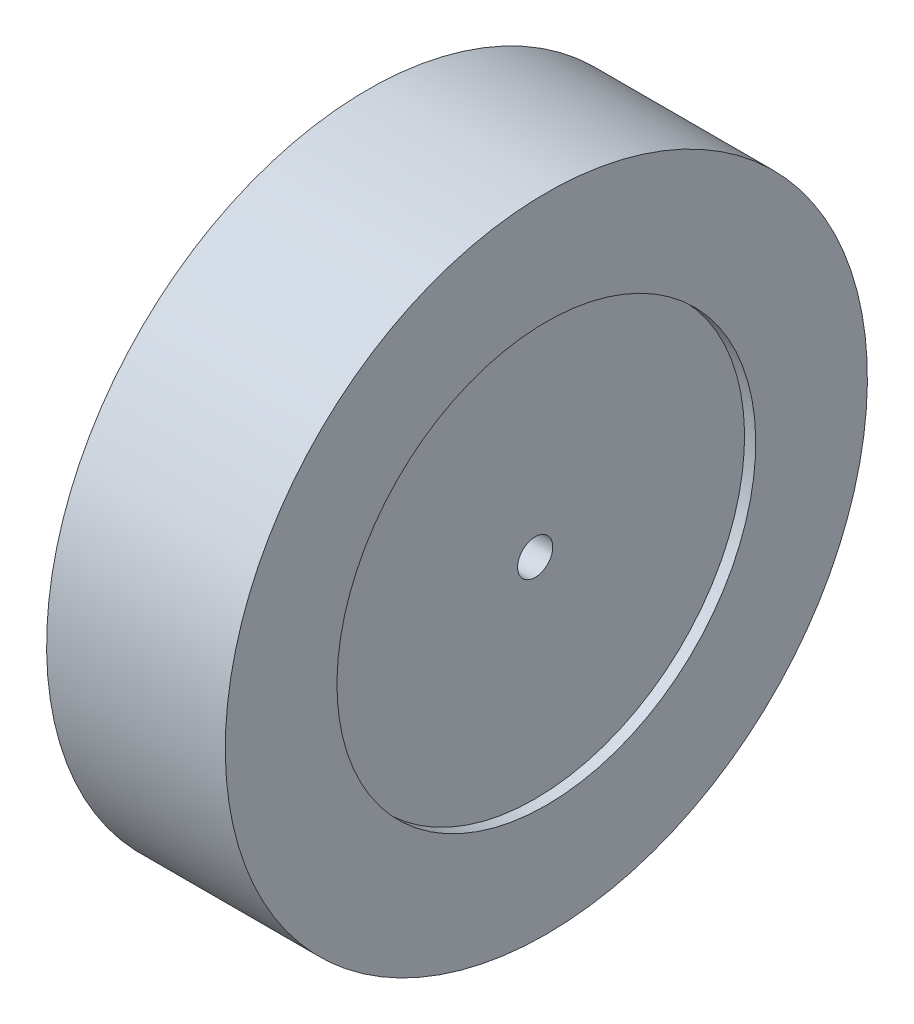
SolidWorks part; units mm, degrees
ref_plane "Front Plane" through (0, 0, 0) normal (0, 0, 1) x (1, 0, 0)
ref_plane "Top Plane" through (0, 0, 0) normal (0, 1, 0) x (1, 0, 0)
ref_plane "Right Plane" through (0, 0, 0) normal (1, 0, 0) x (0, 0, -1)
sketch "Sketch1" plane through (0, 0, 0) normal (0, 0, 1) x (1, 0, 0)
  line L0 (-8.89, 0) -> (8.89, 0)
  line L1 (8.89, 0) -> (8.89, 23.8125)
  line L2 (8.89, 23.8125) -> (10.16, 23.8125)
  line L3 (10.16, 23.8125) -> (10.16, 36.5125)
  line L4 (10.16, 36.5125) -> (-10.16, 36.5125)
  line L5 (0, 36.5125) -> (0, 0) construction
  line L6 (-8.89, 0) -> (-8.89, 23.8125)
  line L7 (-8.89, 23.8125) -> (-10.16, 23.8125)
  line L8 (-10.16, 23.8125) -> (-10.16, 36.5125)
  line L9 (-8.89, 2) -> (8.89, 2)
  point P4 (0, 0)
  dimension "D1" = 20.32
  dimension "D2" = 17.78
  dimension "D3" = 12.7
  dimension "D4" = 36.5125
  dimension "D5" = 2
revolve "Revolve1" add sketch "Sketch1" angle 360 about L0
